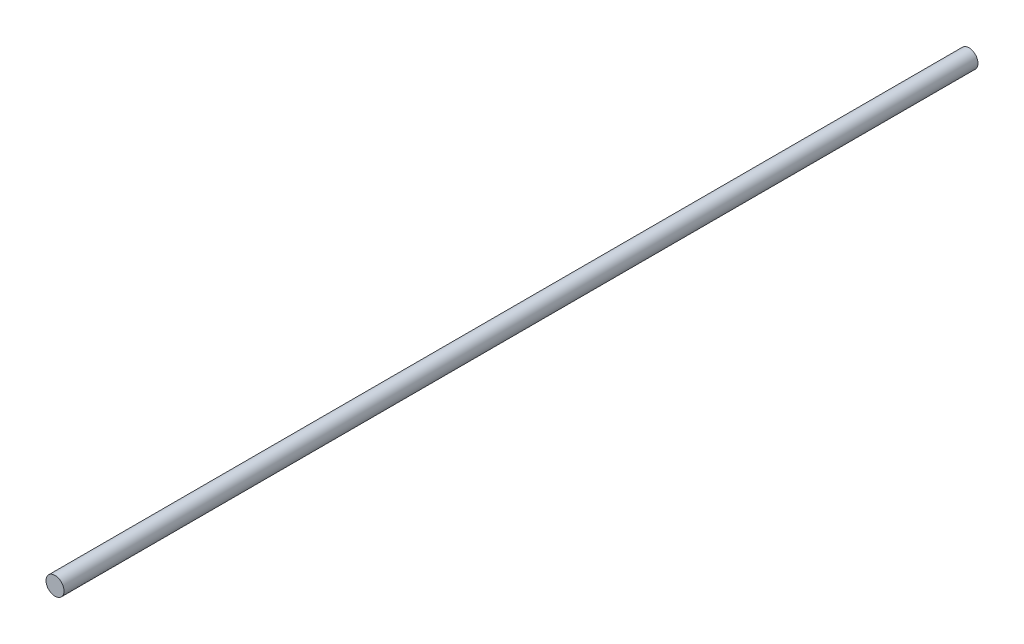
SolidWorks part; units mm, degrees
ref_plane "Front Plane" through (0, 0, 0) normal (0, 0, 1) x (1, 0, 0)
ref_plane "Top Plane" through (0, 0, 0) normal (0, 1, 0) x (1, 0, 0)
ref_plane "Right Plane" through (0, 0, 0) normal (1, 0, 0) x (0, 0, -1)
sketch "Sketch1" plane through (0, 0, 0) normal (0, 0, 1) x (1, 0, 0)
  circle A0 centre (0, 0) radius 4
  dimension "D1" = 8
extrude "Boss-Extrude1" add sketch "Sketch1" along normal blind 405
